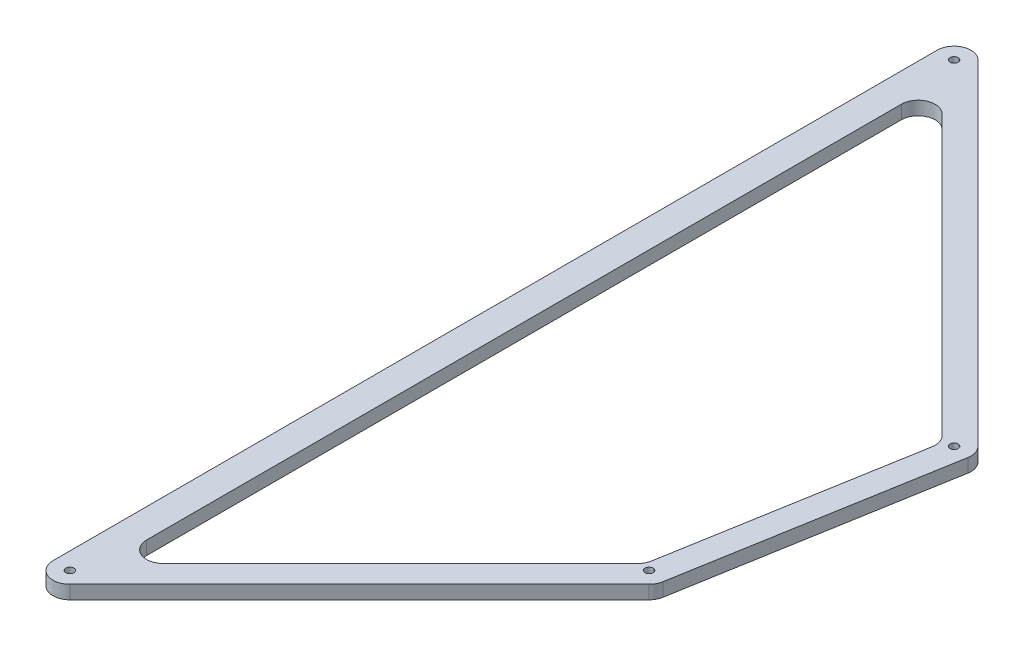
SolidWorks part; units mm, degrees
ref_plane "Front Plane" through (0, 0, 0) normal (0, 0, 1) x (1, 0, 0)
ref_plane "Top Plane" through (0, 0, 0) normal (0, 1, 0) x (1, 0, 0)
ref_plane "Right Plane" through (0, 0, 0) normal (1, 0, 0) x (0, 0, -1)
sketch "Sketch1" plane through (0, 0, 0) normal (0, 1, 0) x (1, 0, 0)
  line L0 (0, 0) -> (0, 165.9636) construction
  line L1 (0, 165.9636) -> (73.66, 165.9636) construction
  line L2 (0, 0) -> (44.958, 0) construction
  line L3 (73.66, 165.9636) -> (44.958, 0) construction
  line L4 (0, 165.9636) -> (62.7994, 103.1642) construction
  line L5 (62.7994, 103.1642) -> (54.3589, 54.3589) construction
  line L6 (54.3589, 54.3589) -> (0, 0) construction
  line L7 (2.2451, 168.2087) -> (65.0444, 105.4093)
  line L8 (65.9279, 102.6232) -> (57.4875, 53.8179)
  line L9 (56.604, 52.1139) -> (2.2451, -2.2451)
  line L10 (-3.175, 165.9636) -> (-3.175, 0)
  line L11 (2.2451, 153.8083) -> (2.2451, 12.1553)
  line L12 (7.6651, 9.9102) -> (52.1685, 54.4136)
  line L13 (53.052, 56.1176) -> (60.8143, 101.0016)
  line L14 (59.9308, 103.7877) -> (7.6651, 156.0534)
  arc A0 (65.0444, 105.4093) -> (65.9279, 102.6232) centre (62.7994, 103.1642) cw
  arc A1 (57.4875, 53.8179) -> (56.604, 52.1139) centre (54.3589, 54.3589) cw
  arc A2 (2.2451, -2.2451) -> (-3.175, 0) centre (0, 0) cw
  arc A3 (-3.175, 165.9636) -> (2.2451, 168.2087) centre (0, 165.9636) cw
  circle A4 centre (0, 0) radius 0.762
  circle A5 centre (54.3589, 54.3589) radius 0.762
  circle A6 centre (62.7994, 103.1642) radius 0.762
  circle A7 centre (0, 165.9636) radius 0.762
  arc A8 (7.6651, 9.9102) -> (2.2451, 12.1553) centre (5.4201, 12.1553) cw
  arc A9 (60.8143, 101.0016) -> (59.9308, 103.7877) centre (57.6857, 101.5427) ccw
  arc A10 (52.1685, 54.4136) -> (53.052, 56.1176) centre (49.9234, 56.6586) ccw
  arc A11 (2.2451, 153.8083) -> (7.6651, 156.0534) centre (5.4201, 153.8083) cw
  dimension "D9" = 3.175
  dimension "D10" = 1.524
  dimension "D14" = 3.175
  dimension "D1" = 165.9636
  dimension "D2" = 73.66
  dimension "D3" = 44.958
  dimension "D4" = 3.175
  dimension "D5" = 3.175
  dimension "D6" = 3.175
  dimension "D7" = 3.175
  dimension "D8" = 45
  dimension "D11" = 3.175
  dimension "D12" = 3.175
  dimension "D13" = 3.175
extrude "Boss-Extrude1" add sketch "Sketch1" along normal blind 2.54
